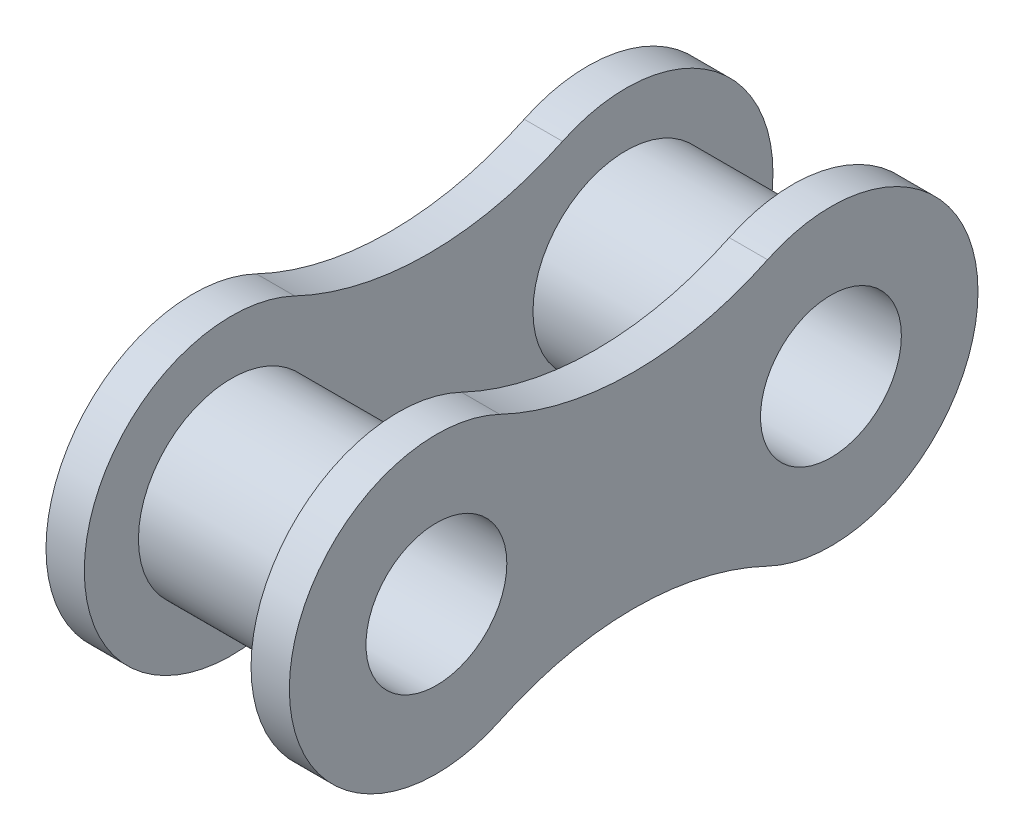
SolidWorks part; units mm, degrees
material "AISI 304"
ref_plane "Спереди" through (0, 0, 0) normal (0, 0, 1) x (1, 0, 0)
ref_plane "Сверху" through (0, 0, 0) normal (0, 1, 0) x (1, 0, 0)
ref_plane "Справа" through (0, 0, 0) normal (1, 0, 0) x (0, 0, -1)
other "Configuration Table"
sketch "Эскиз1" plane through (0, 0, 0) normal (1, 0, 0) x (0, 0, -1)
  line L0 (-19.05, 0) -> (19.05, 0) construction
  circle A0 centre (-19.05, 0) radius 6.8
  circle A1 centre (19.05, 0) radius 6.8
  circle A2 centre (-19.05, 0) radius 8.975
  circle A3 centre (19.05, 0) radius 8.975
  point P4 (0, 0)
  dimension "D2" = 17.95
  dimension "D3" = 13.6
  dimension "D1" = 38.1
extrude "Бобышка-Вытянуть1" add sketch "Эскиз1" along normal mid plane 23.5
sketch "Эскиз3" plane through (11.75, 0, 0) normal (1, 0, 0) x (0, 0, -1)
  line L0 (0, 50) -> (0, -50) construction
  circle A0 centre (-19.05, 0) radius 8.975
  circle A1 centre (19.05, 0) radius 8.975
  arc A2 (12.9299, -12.8134) -> (12.9299, 12.8134) centre (19.05, 0) ccw
  arc A3 (-12.9299, 12.8134) -> (-12.9299, -12.8134) centre (-19.05, 0) ccw
  arc A4 (-12.9299, 12.8134) -> (12.9299, 12.8134) centre (0, 39.8841) ccw
  arc A5 (12.9299, -12.8134) -> (-12.9299, -12.8134) centre (0, -39.8841) ccw
  dimension "D1" = 60
  dimension "D2" = 28.4
  dimension "D3" = 17.95
extrude "Бобышка-Вытянуть4" add sketch "Эскиз3" against normal blind 3.7
mirror "Зеркальное отражение10" about plane through (0, 0, 0) normal (1, 0, 0) of "Бобышка-Вытянуть4"
